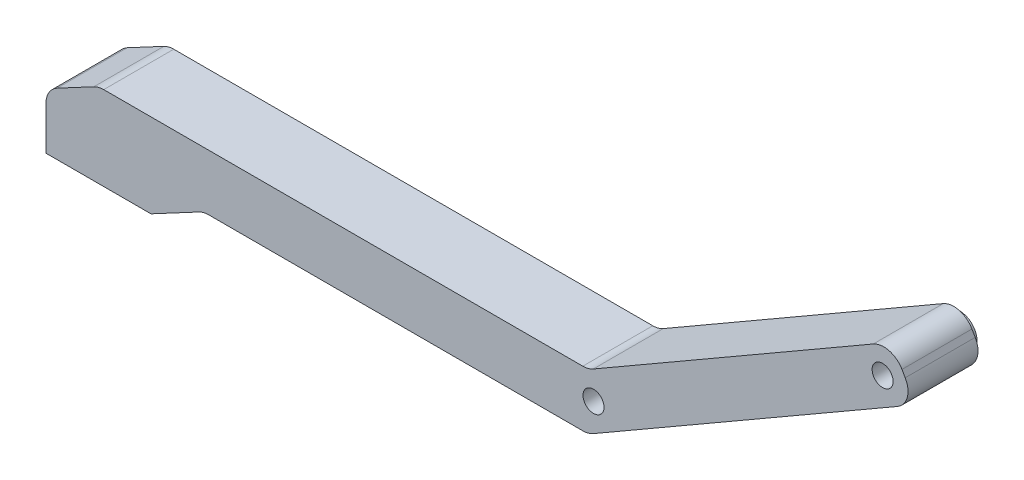
SolidWorks part; units mm, degrees
ref_plane "前视基准面" through (0, 0, 0) normal (0, 0, 1) x (1, 0, 0)
ref_plane "上视基准面" through (0, 0, 0) normal (0, 1, 0) x (1, 0, 0)
ref_plane "右视基准面" through (0, 0, 0) normal (1, 0, 0) x (0, 0, -1)
sketch "草图1" plane through (0, 0, 0) normal (0, 0, 1) x (1, 0, 0)
  line L2 (-7.5, 4) -> (-7.5, -4)
  line L3 (-7.5, -4) -> (7.5, -4)
  line L5 (-7.5, 4) -> (7.5, -4) construction
  line L6 (-7.5, -4) -> (7.5, 4) construction
  line L8 (0, 8) -> (70, 8)
  line L10 (0, 8) -> (-7.5, 4)
  line L11 (7.5, -4) -> (15, 0)
  line L12 (70, 0) -> (116.7654, 27)
  line L13 (116.7654, 27) -> (113.3013, 33)
  line L14 (70, 8) -> (113.3013, 33)
  line L15 (15, 0) -> (70, 0)
  circle A0 centre (112.0369, 28.27) radius 1.5
  circle A1 centre (70.7275, 4.42) radius 1.5
  point P0 (0, 0)
extrude "凸台-拉伸1" add sketch "草图1" along normal blind 10
fillet "圆角1" radius 3 7 edges at (15, 0, 5) (113.3013, 33, 5) (116.7654, 27, 5) (70, 0, 5) (70, 8, 5) (0, 8, 5) (-7.5, 4, 5)
sketch "草图2" plane through (0, 0, 10) normal (0, 0, 1) x (1, 0, 0)
  circle A1 centre (112.0369, 28.27) radius 2.5
  circle A3 centre (112.0369, 28.27) radius 1.5
extrude "凸台-拉伸2" add sketch "草图2" against normal blind 11
